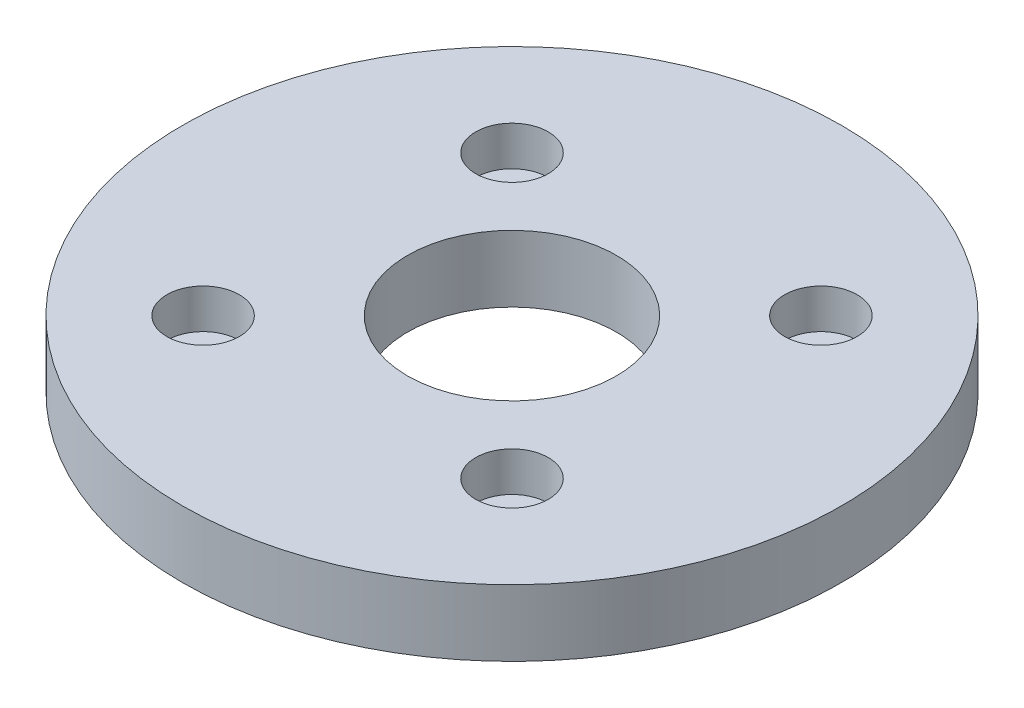
SolidWorks part; units mm, degrees
ref_plane "前视基准面" through (0, 0, 0) normal (0, 0, 1) x (1, 0, 0)
ref_plane "上视基准面" through (0, 0, 0) normal (0, 1, 0) x (1, 0, 0)
ref_plane "右视基准面" through (0, 0, 0) normal (1, 0, 0) x (0, 0, -1)
sketch "草图1" plane through (0, 0, 0) normal (0, 1, 0) x (1, 0, 0)
  circle A0 centre (0, 0) radius 16.35
  circle A1 centre (0, 0) radius 5.5
  circle A2 centre (0, 0) radius 15 construction
  circle A3 centre (0, 0) radius 23
  circle A4 centre (0, 0) radius 17.35
  dimension "D1" = 32.7
  dimension "D2" = 11
  dimension "D3" = 30
  dimension "D4" = 46
  dimension "D5" = 34.7
extrude "凸台-拉伸1" add sketch "草图1" along normal blind 3.5 contours A1 | A4
sketch "草图3" plane through (0, 0, 0) normal (0, 1, 0) x (1, 0, 0)
  circle A0 centre (0, 0) radius 23 construction
  circle A1 centre (0, 0) radius 23
  circle A2 centre (0, 0) radius 17.35 construction
  circle A3 centre (0, 0) radius 17.35
sketch "草图4" plane through (0, 0, 0) normal (0, 1, 0) x (1, 0, 0)
  circle A0 centre (0, 0) radius 5.5 construction
  circle A1 centre (0, 0) radius 5.5
sketch "草图6" plane through (0, 0, 0) normal (0, 1, 0) x (1, 0, 0)
  line L0 (-23.1107, 23.1107) -> (0, 0) construction
  line L1 (0, 0) -> (22.5537, 22.5537) construction
  circle A0 centre (0, 0) radius 16.35 construction
  circle A1 centre (0, 0) radius 16.35 construction
  circle A2 centre (0, 0) radius 17.35 construction
  circle A3 centre (0, 0) radius 17.35 construction
  circle A4 centre (8.1317, 8.1317) radius 1
  circle A5 centre (7.4246, -7.4246) radius 1
  circle A6 centre (-8.1317, -8.1317) radius 1
  circle A7 centre (-7.4246, 7.4246) radius 1
  circle A8 centre (0, 0) radius 5.5 construction
  circle A9 centre (0, 0) radius 5.5 construction
  dimension "D1" = 32.7
  dimension "D2" = 34.7
  dimension "D3" = 2
  dimension "D4" = 2
  dimension "D5" = 2
  dimension "D6" = 2
  dimension "D7" = 11
  dimension "D8" = 10.5
  dimension "D9" = 10.5
  dimension "D10" = 11.5
  dimension "D11" = 11.5
extrude "切除-拉伸3" cut sketch "草图6" against normal mid plane 10
sketch "草图7" plane through (0, 3.5, 0) normal (0, 1, 0) x (1, 0, 0)
  circle A0 centre (-7.4246, 7.4246) radius 1 construction
  circle A1 centre (-7.4246, 7.4246) radius 1 construction
  circle A2 centre (8.1317, 8.1317) radius 1 construction
  circle A3 centre (8.1317, 8.1317) radius 1 construction
  circle A4 centre (-8.1317, -8.1317) radius 1 construction
  circle A5 centre (-8.1317, -8.1317) radius 1 construction
  circle A6 centre (7.4246, -7.4246) radius 1 construction
  circle A7 centre (7.4246, -7.4246) radius 1 construction
  circle A8 centre (-7.4246, 7.4246) radius 1.91
  circle A9 centre (8.1317, 8.1317) radius 1.91
  circle A10 centre (7.4246, -7.4246) radius 1.91
  circle A11 centre (-8.1317, -8.1317) radius 1.91
  dimension "D1" = 3.82
  dimension "D2" = 3.82
  dimension "D3" = 3.82
  dimension "D4" = 3.82
extrude "切除-拉伸4" cut sketch "草图7" against normal blind 2.08
